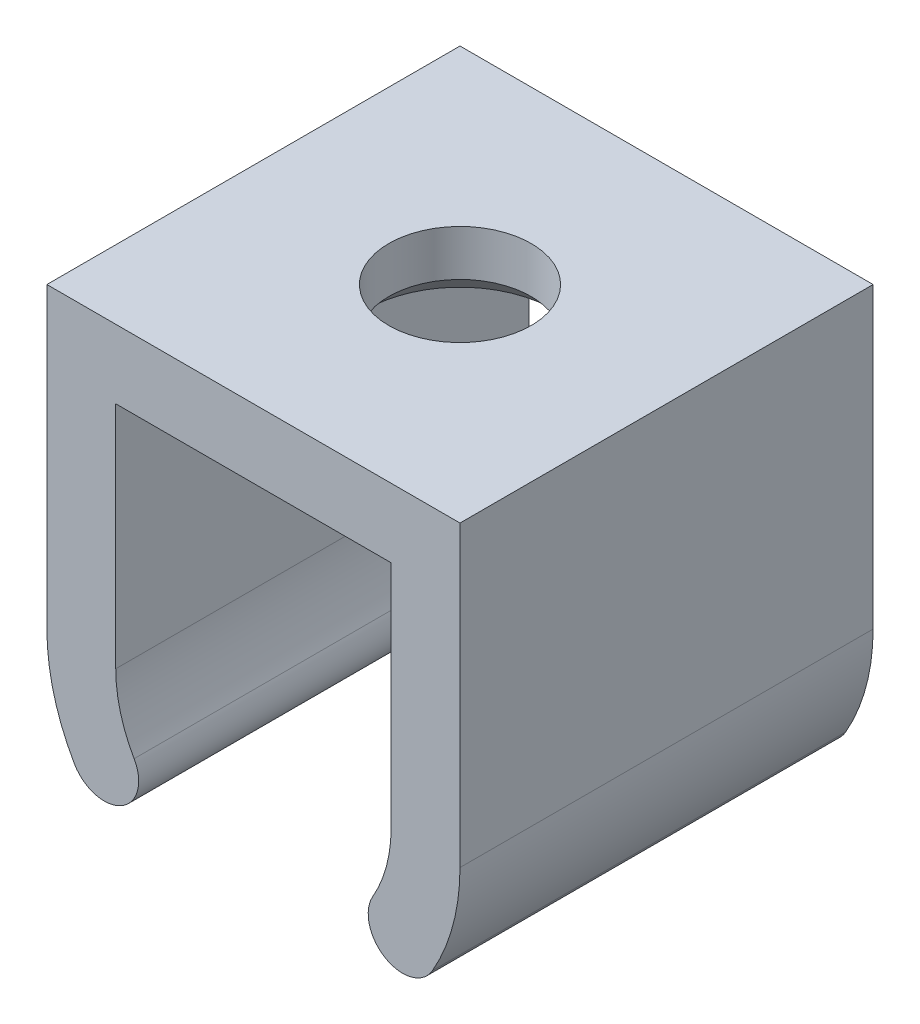
SolidWorks part; units mm, degrees
ref_plane "Ebene vorne" through (0, 0, 0) normal (0, 0, 1) x (1, 0, 0)
ref_plane "Ebene oben" through (0, 0, 0) normal (0, 1, 0) x (1, 0, 0)
ref_plane "Ebene rechts" through (0, 0, 0) normal (1, 0, 0) x (0, 0, -1)
sketch "Skizze1" plane through (0, 0, 0) normal (0, 0, 1) x (1, 0, 0)
  line L0 (-4.5, 6.5) -> (4.5, 6.5)
  line L1 (4.5, 6.5) -> (4.5, 0)
  line L2 (-4.5, 0) -> (-4.5, 6.5)
  arc A0 (2.6, -1.4967) -> (-2.6, -1.4967) centre (0, 0) ccw
  arc A1 (4.5, 0) -> (3.9, -2.245) centre (0, 0) cw
  arc A2 (-3.9, -2.245) -> (-2.6, -1.4967) centre (-3.25, -1.8708) ccw
  arc A3 (2.6, -1.4967) -> (3.9, -2.245) centre (3.25, -1.8708) ccw
  arc A4 (-3.9, -2.245) -> (-4.5, 0) centre (0, 0) cw
  point P11 (1.5584, -2.9553)
  dimension "D1" = 6
  dimension "D3" = 3.5
  dimension "D4" = 5
  dimension "D2" = 1.5
extrude "Aufsatz-Linear austragen1" add sketch "Skizze1" along normal mid plane 9
sketch "Skizze3" plane through (0, 6.5, 0) normal (0, 1, 0) x (1, 0, 0)
  circle A0 centre (0, 0) radius 1.55
  dimension "D1" = 3.1
extrude "Schnitt-Linear austragen1" cut sketch "Skizze3" against normal up to next
sketch "Skizze4" plane through (0, 0, 4.5) normal (0, 0, 1) x (1, 0, 0)
  line L0 (-3, 0) -> (-3, 5)
  line L1 (-3, 5) -> (3, 5)
  line L2 (3, 5) -> (3, 0)
  line L3 (3, 0) -> (-3, 0)
  arc A0 (2.6, -1.4967) -> (-2.6, -1.4967) centre (0, 0) ccw construction
  dimension "D1" = 2
extrude "Schnitt-Linear austragen2" cut sketch "Skizze4" against normal through all both and the other way through all
chamfer "Fase1" distance 0.5 angle 45 1 edges at (0, 5, 1.55)
